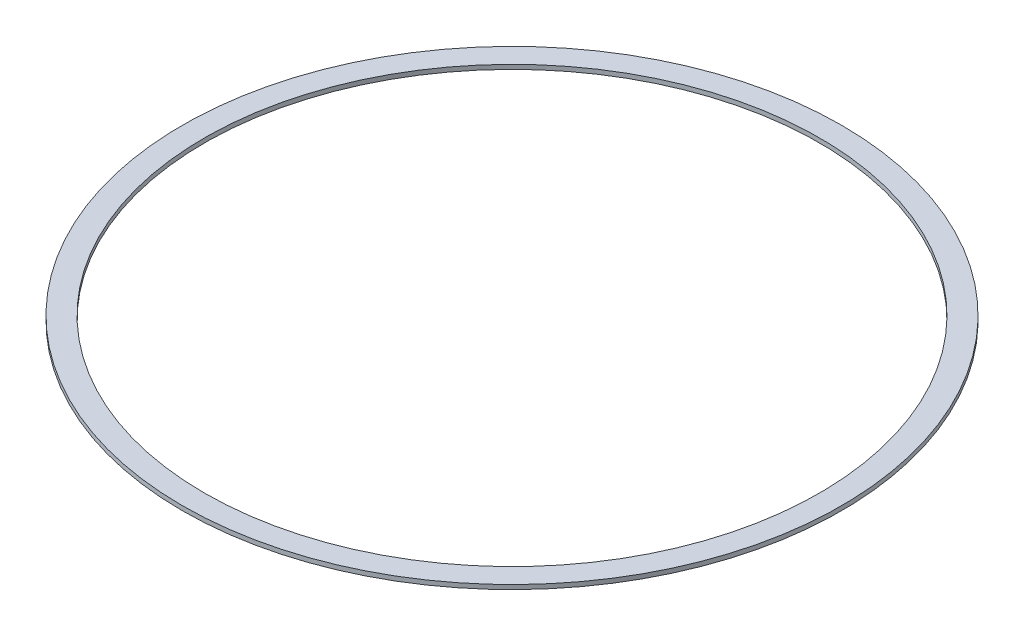
SolidWorks part; units mm, degrees
ref_plane "Front Plane" through (0, 0, 0) normal (0, 0, 1) x (1, 0, 0)
ref_plane "Top Plane" through (0, 0, 0) normal (0, 1, 0) x (1, 0, 0)
ref_plane "Right Plane" through (0, 0, 0) normal (1, 0, 0) x (0, 0, -1)
sketch "Sketch1" plane through (0, 0, 0) normal (0, 1, 0) x (1, 0, 0)
  line L0 (-210, 0) -> (210, 0) construction
  circle A0 centre (0, 0) radius 210
  circle A1 centre (0, 0) radius 225
  dimension "D1" = 420
  dimension "D2" = 450
extrude "Boss-Extrude1" add sketch "Sketch1" along normal mid plane 3
